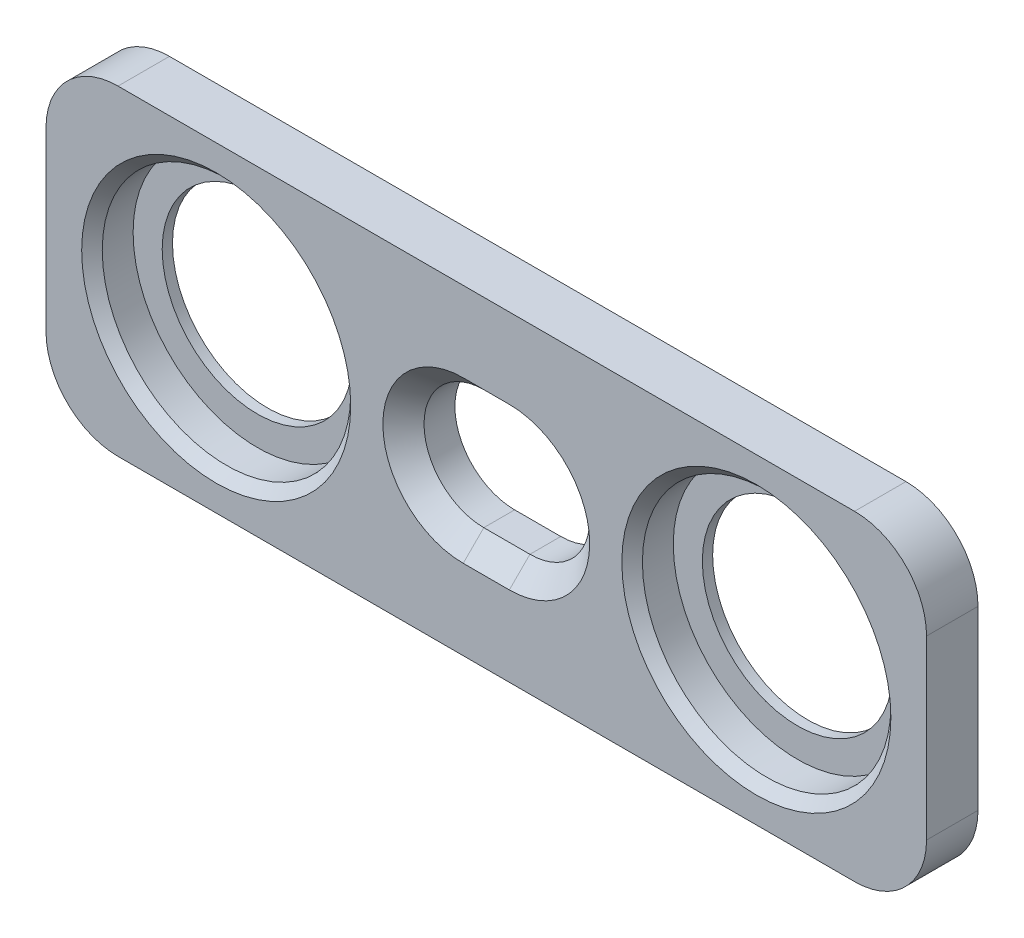
SolidWorks part; units mm, degrees
ref_plane "Alzado" through (0, 0, 0) normal (0, 0, 1) x (1, 0, 0)
ref_plane "Planta" through (0, 0, 0) normal (0, 1, 0) x (1, 0, 0)
ref_plane "Vista lateral" through (0, 0, 0) normal (1, 0, 0) x (0, 0, -1)
sketch "Croquis1" plane through (0, 0, 0) normal (0, 0, 1) x (1, 0, 0)
  line L0 (0, 23.9911) -> (0, -22.7284) construction
  line L1 (-42.792, 15.5862) -> (42.792, 15.5862)
  line L2 (-42.792, 15.5862) -> (-42.792, -15.5862)
  line L3 (-42.792, -15.5862) -> (42.792, -15.5862)
  line L4 (42.792, 15.5862) -> (42.792, -15.5862)
  line L5 (-42.792, 15.5862) -> (42.792, -15.5862) construction
  line L6 (-42.792, -15.5862) -> (42.792, 15.5862) construction
  circle A0 centre (-26.25, 0) radius 12.075
  circle A1 centre (26.25, 0) radius 12.075
  point P0 (0, 0)
  dimension "D1" = 24.15
  dimension "D2" = 52.5
extrude "Saliente-Extruir1" add sketch "Croquis1" along normal blind 5
sketch "Croquis2" plane through (0, 0, 0) normal (0, 0, -1) x (-1, 0, 0)
  line L1 (42.792, -15.5862) -> (-42.792, -15.5862)
  line L2 (42.792, -15.5862) -> (42.792, 15.5862)
  line L3 (42.792, 15.5862) -> (-42.792, 15.5862)
  line L4 (-42.792, -15.5862) -> (-42.792, 15.5862)
  line L5 (42.792, -15.5862) -> (-42.792, 15.5862) construction
  line L6 (42.792, 15.5862) -> (-42.792, -15.5862) construction
  circle A0 centre (-26.25, 0) radius 9.25
  circle A1 centre (26.25, 0) radius 9.25
  point P0 (0, 0)
  dimension "D1" = 18.5
extrude "Saliente-Extruir2" add sketch "Croquis2" against normal blind 1
fillet "Redondeo1" radius 7 4 edges at (-42.792, -15.5862, 2.5) (42.792, -15.5862, 2.5) (42.792, 15.5862, 2.5) (-42.792, 15.5862, 2.5)
sketch "Croquis3" plane through (0, 0, 5) normal (0, 0, 1) x (1, 0, 0)
  line L0 (-2.2415, 0) -> (2.2415, 0) construction
  line L1 (-2.2415, 5.8087) -> (2.2415, 5.8087)
  line L2 (-2.2415, -5.8087) -> (2.2415, -5.8087)
  arc A0 (-2.2415, 5.8087) -> (-2.2415, -5.8087) centre (-2.2415, 0) ccw
  arc A1 (2.2415, -5.8087) -> (2.2415, 5.8087) centre (2.2415, 0) ccw
  point P2 (0, 0)
extrude "Cortar-Extruir1" cut sketch "Croquis3" against normal through all
chamfer "Chaflán1" distance 2 angle 45 4 edges at (0, -5.8087, 5) (8.0502, 0, 5) (-8.0502, 0, 5) (0, 5.8087, 5)
chamfer "Chaflán2" distance 1 angle 45 2 edges at (38.325, 0, 5) (-14.175, 0, 5)
